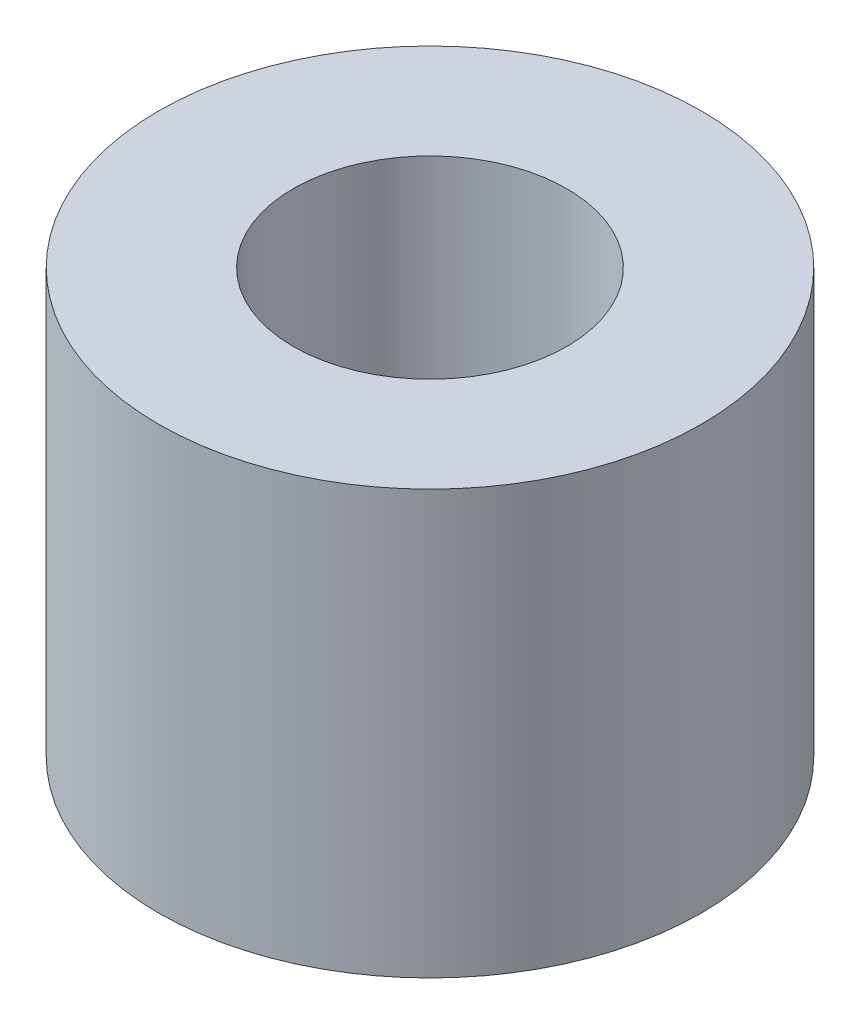
SolidWorks part; units mm, degrees
ref_plane "Front Plane" through (0, 0, 0) normal (0, 0, 1) x (1, 0, 0)
ref_plane "Top Plane" through (0, 0, 0) normal (0, 1, 0) x (1, 0, 0)
ref_plane "Right Plane" through (0, 0, 0) normal (1, 0, 0) x (0, 0, -1)
sketch "Sketch1" plane through (0, 0, 0) normal (0, 1, 0) x (1, 0, 0)
  circle A0 centre (0, 0) radius 6.25
  circle A1 centre (0, 0) radius 3.15
  dimension "D1" = 12.5
  dimension "D2" = 6.3
extrude "Boss-Extrude1" add sketch "Sketch1" along normal blind 9.75
